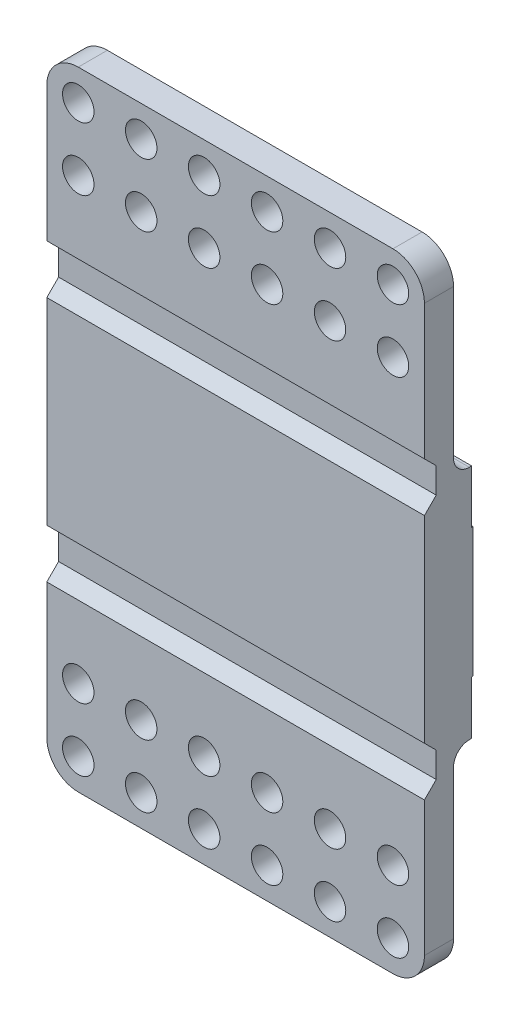
SolidWorks part; units mm, degrees
ref_plane "Plan de face" through (0, 0, 0) normal (0, 0, 1) x (1, 0, 0)
ref_plane "Plan de dessus" through (0, 0, 0) normal (0, 1, 0) x (1, 0, 0)
ref_plane "Plan de droite" through (0, 0, 0) normal (1, 0, 0) x (0, 0, -1)
sketch "Esquisse1" plane through (0, 0, 0) normal (0, 0, 1) x (1, 0, 0)
  line L0 (24, 39.9) -> (-24, -39.9) construction
  line L1 (-20, 39.9) -> (20, 39.9)
  line L2 (-24, 35.9) -> (-24, -35.9)
  line L3 (-20, -39.9) -> (20, -39.9)
  line L4 (24, 35.9) -> (24, -35.9)
  arc A0 (-24, -35.9) -> (-20, -39.9) centre (-20, -35.9) ccw
  arc A1 (20, -39.9) -> (24, -35.9) centre (20, -35.9) ccw
  arc A2 (20, 39.9) -> (24, 35.9) centre (20, 35.9) cw
  arc A3 (-20, 39.9) -> (-24, 35.9) centre (-20, 35.9) ccw
  point P4 (23.2071, 12.819)
  point P5 (-24, 23.3957)
  point P8 (0, 0)
  point P18 (-24, 39.9)
  dimension "D3" = 4
  dimension "D1" = 48
  dimension "D2" = 79.8
extrude "Boss.-Extru.1" add sketch "Esquisse1" along normal blind 3.7
sketch "Esquisse2" plane through (0, 0, 3.7) normal (0, 0, 1) x (1, 0, 0)
  line L0 (20, 35.97) -> (20, 27.97) construction
  line L1 (20, 39.9) -> (-20, 39.9) construction
  line L2 (20, 37.97) -> (20, 39.9) construction
  line L3 (20, 31.97) -> (24, 31.97) construction
  line L4 (24, -35.9) -> (24, 35.9) construction
  circle A0 centre (20, 35.97) radius 2
  circle A1 centre (20, 27.97) radius 2
  dimension "D4" = 4
  dimension "D1" = 8
  dimension "D2" = 1.93
  dimension "D3" = 4
extrude "Enlèv. mat.-Extru.1" cut sketch "Esquisse2" against normal through all
pattern_linear "Répétition linéaire1" count 6 spacing 8 along (-1, 0, 0) of "Enlèv. mat.-Extru.1"
mirror "Symétrie1" about plane through (0, 0, 0) normal (0, 1, 0) of "Répétition linéaire1", "Enlèv. mat.-Extru.1"
sketch "Esquisse3" plane through (0, 0, 0) normal (1, 0, 0) x (0, 0, -1)
  line L0 (0, 35.9) -> (0, -35.9) construction
  line L1 (0, 15) -> (0, 0)
  line L2 (0, 15) -> (2.3, 15)
  line L3 (2.3, 15) -> (2.3, 0)
  line L4 (2.3, 0) -> (0, 0)
  line L5 (-3.7, 35.9) -> (-3.7, -35.9) construction
  point P9 (2.3, 14.5379)
  dimension "D1" = 6
  dimension "D2" = 15
extrude "Boss.-Extru.2" add sketch "Esquisse3" along normal through all and the other way through all
fillet "Congé1" radius 2 1 edges at (0, 15, 0)
mirror "Symétrie2" about plane through (0, 0, 0) normal (0, 1, 0) of "Boss.-Extru.2", "Congé1"
sketch "Esquisse4" plane through (-24, 0, 0) normal (-1, 0, 0) x (0, 0, 1)
  line L0 (3.7, 18.7752) -> (2.2, 17.2752)
  line L1 (3.7, 35.9) -> (3.7, -35.9) construction
  line L2 (2.2, 17.2752) -> (2.2, 14.0318)
  line L3 (2.2, 14.0318) -> (3.7, 12.5318)
  line L4 (3.7, 12.5318) -> (3.7, 18.7752)
  point P4 (3.7, 8.111)
  point P7 (3.7, 18.7752)
  point P8 (3.7, 12.5318)
  dimension "D1" = 1.5
  dimension "D2" = 45
extrude "Enlèv. mat.-Extru.2" cut sketch "Esquisse4" against normal through all
mirror "Symétrie3" about plane through (0, 0, 0) normal (0, 1, 0) of "Enlèv. mat.-Extru.2"
sketch "Esquisse5" plane through (24, 0, 0) normal (1, 0, 0) x (0, 0, -1)
  line L0 (2.3, -15) -> (2.3, 15) construction
  line L1 (2.3, -8.2212) -> (2.5, -8.2212)
  line L2 (2.3, -8.2212) -> (2.3, 8.2172)
  line L3 (2.3, 8.2172) -> (2.5, 8.2172)
  line L4 (2.5, -8.2212) -> (2.5, 8.2172)
extrude "Boss.-Extru.3" add sketch "Esquisse5" against normal through all
